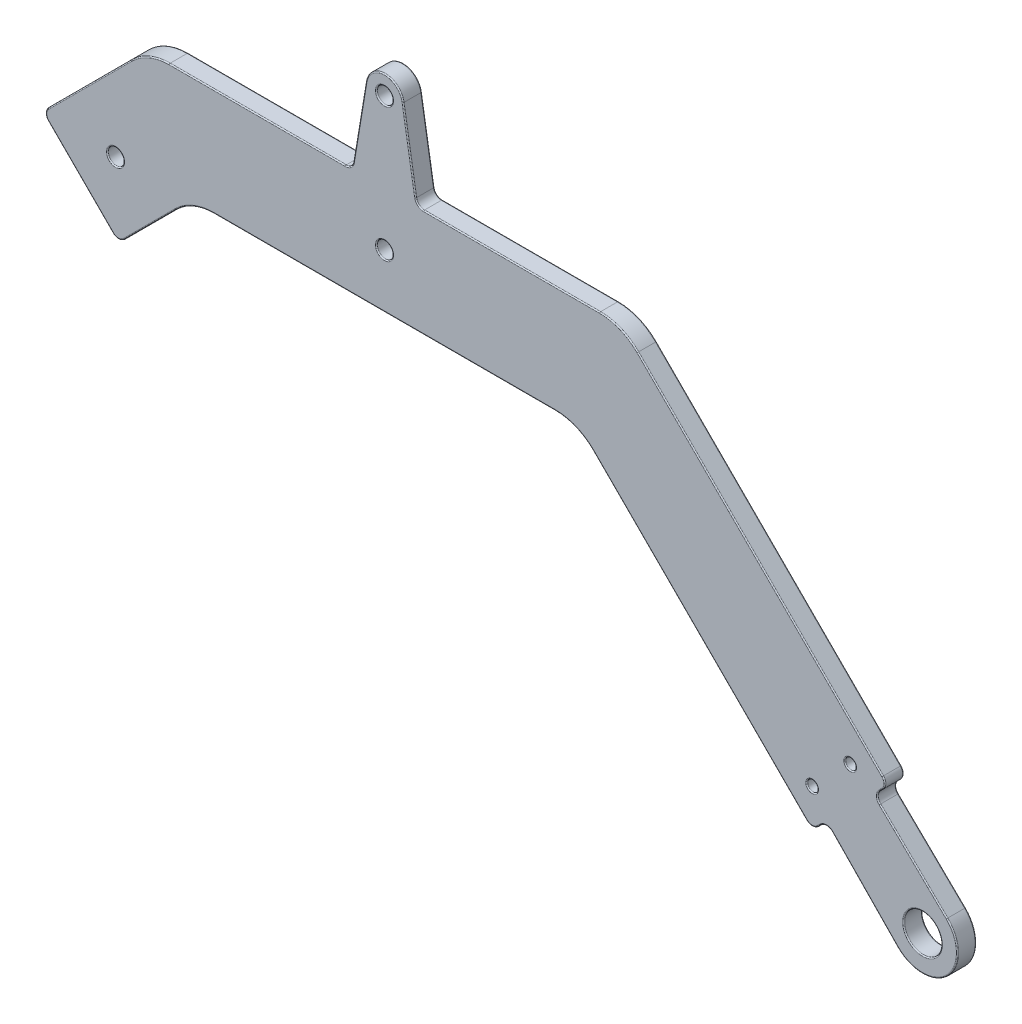
SolidWorks part; units mm, degrees
ref_plane "Front Plane" through (0, 0, 0) normal (0, 0, 1) x (1, 0, 0)
ref_plane "Top Plane" through (0, 0, 0) normal (0, 1, 0) x (1, 0, 0)
ref_plane "Right Plane" through (0, 0, 0) normal (1, 0, 0) x (0, 0, -1)
sketch "Sketch1" plane through (0, 0, 0) normal (0, 0, 1) x (1, 0, 0)
  line L0 (-100, 0) -> (100, 0) construction
  line L1 (-100, 0) -> (0, 100) construction
  line L2 (0, 100) -> (100, 0) construction
  line L3 (0, 0) -> (-50, 50) construction
  line L4 (-40, 60) -> (40, 60) construction
  line L5 (0, 100) -> (0, 60) construction
  circle A0 centre (-100, 0) radius 20
  circle A1 centre (0, 0) radius 20
  circle A2 centre (100, 0) radius 20
  point P2 (0, 0)
  dimension "D5" = 40
  dimension "D1" = 200
  dimension "D2" = 90
  dimension "D3" = 90
  dimension "D4" = 80
sketch "Sketch2" plane through (0, 0, 0) normal (0, 0, 1) x (1, 0, 0)
  line L0 (-56.5165, 43.4835) -> (-40, 60) construction
  line L1 (-100, 0) -> (0, 100) construction
  line L2 (-40, 60) -> (40, 60) construction
  line L3 (40, 60) -> (86.565, 13.435) construction
  line L4 (0, 100) -> (100, 0) construction
  line L5 (-49.4454, 36.4124) -> (-35.8579, 50)
  line L6 (-35.8579, 50) -> (35.8579, 50)
  line L7 (35.8579, 50) -> (79.4939, 6.364)
  line L8 (-63.5876, 50.5546) -> (-44.1421, 70)
  line L9 (-44.1421, 70) -> (44.1421, 70)
  line L10 (44.1421, 70) -> (93.636, 20.5061)
  line L11 (-63.5876, 50.5546) -> (-49.4454, 36.4124)
  line L12 (93.636, 20.5061) -> (79.4939, 6.364)
  line L13 (90.9809, 17.8509) -> (104.534, 4.6576)
  line L14 (82.1491, 9.0191) -> (95.3424, -4.534)
  line L15 (90.1005, 24.0416) -> (75.9584, 9.8995)
  line L16 (0, 100) -> (0, 60) construction
  line L17 (-6, 70) -> (-3.4532, 85.4203)
  line L18 (6, 70) -> (3.4532, 85.4203)
  circle A0 centre (100, 0) radius 3.5
  circle A1 centre (100, 0) radius 10 construction
  arc A2 (95.3424, -4.534) -> (104.534, 4.6576) centre (100, 0) ccw
  circle A3 centre (100, 0) radius 0.5
  circle A4 centre (100, 0) radius 20 construction
  circle A5 centre (100, 0) radius 6.5 construction
  circle A6 centre (79.4939, 13.435) radius 1
  circle A7 centre (86.565, 20.5061) radius 1
  circle A8 centre (0, 60) radius 1.5
  circle A9 centre (0, 84.85) radius 1.5
  arc A10 (3.4532, 85.4203) -> (-3.4532, 85.4203) centre (0, 84.85) ccw
  circle A11 centre (0, 84.85) radius 3.5 construction
  circle A12 centre (-50, 50) radius 1.5
  point P51 (0, 0)
  dimension "D4" = 20
  dimension "D5" = 7
  dimension "D10" = 2
  dimension "D13" = 3
  dimension "D18" = 3
  dimension "D3" = 27.5
  dimension "D8" = 19
  dimension "D9" = 5
  dimension "D11" = 5
  dimension "D12" = 5
  dimension "D14" = 14.85
  dimension "D16" = 6
  dimension "D17" = 6
  dimension "D1" = 10
  dimension "D2" = 10
  dimension "D6" = 3
  dimension "D7" = 3
  dimension "D15" = 2
sketch "Sketch3" plane through (0, 0, 0) normal (0, 0, 1) x (1, 0, 0)
  line L1 (-100, 0) -> (0, 100) construction
  line L2 (-86.565, 13.435) -> (-50, 50) construction
  line L3 (-50, 50) -> (-13.435, 13.435) construction
  line L4 (0, 0) -> (-50, 50) construction
  line L5 (-93.636, 20.5061) -> (-50, 64.1421)
  line L6 (-50, 64.1421) -> (-6.364, 20.5061)
  line L7 (-79.4939, 6.364) -> (-50, 35.8579)
  line L8 (-50, 35.8579) -> (-20.5061, 6.364)
  line L9 (-93.636, 20.5061) -> (-50, 64.1421) construction
  line L10 (-79.4939, 6.364) -> (-50, 35.8579) construction
  line L11 (-93.636, 20.5061) -> (-79.4939, 6.364)
  line L12 (-6.364, 20.5061) -> (-20.5061, 6.364)
  line L13 (-104.5962, 4.5962) -> (-91.2218, 17.9706)
  line L14 (-95.4038, -4.5962) -> (-82.0294, 8.7782)
  line L15 (-17.9706, 8.7782) -> (-4.5962, -4.5962)
  line L16 (-8.7782, 17.9706) -> (4.5962, 4.5962)
  line L17 (-90.1005, 24.0416) -> (-75.9584, 9.8995) construction
  line L18 (-24.0416, 9.8995) -> (-9.8995, 24.0416) construction
  circle A0 centre (-100, 0) radius 10 construction
  circle A1 centre (-100, 0) radius 3.5
  circle A2 centre (0, 0) radius 3.5
  circle A3 centre (0, 0) radius 10 construction
  arc A4 (-4.5962, -4.5962) -> (4.5962, 4.5962) centre (0, 0) ccw
  arc A5 (-104.5962, 4.5962) -> (-95.4038, -4.5962) centre (-100, 0) ccw
  circle A6 centre (-86.565, 20.5061) radius 1
  circle A7 centre (-100, 0) radius 20 construction
  circle A8 centre (0, 0) radius 20 construction
  circle A9 centre (-100, 0) radius 6.5 construction
  circle A10 centre (0, 0) radius 6.5 construction
  circle A11 centre (-79.4939, 13.435) radius 1
  circle A12 centre (-20.5061, 13.435) radius 1
  circle A13 centre (-13.435, 20.5061) radius 1
  circle A14 centre (-50, 50) radius 1.5 construction
  circle A15 centre (-50, 50) radius 1.5
  point P55 (0, 0)
  dimension "D1" = 20
  dimension "D2" = 7
  dimension "D8" = 2
  dimension "D6" = 19
  dimension "D7" = 19
  dimension "D9" = 5
  dimension "D10" = 5
  dimension "D11" = 5
  dimension "D12" = 5
  dimension "D13" = 5
  dimension "D14" = 5
  dimension "D3" = 3
  dimension "D4" = 10
  dimension "D5" = 10
sketch "Sketch4" plane through (0, 0, 0) normal (0, 0, 1) x (1, 0, 0)
  line L0 (-57.5, 94.8011) -> (57.5, 94.8011)
  line L1 (57.5, 94.8011) -> (57.5, 84.8011)
  line L2 (57.5, 84.8011) -> (44.1421, 70)
  line L3 (44.1421, 70) -> (-44.1421, 70)
  line L4 (-44.1421, 70) -> (-57.5, 84.8011)
  line L5 (-57.5, 84.8011) -> (-57.5, 94.8011)
  line L6 (4, 60) -> (4, 70)
  line L7 (-4, 60) -> (-4, 70)
  line L9 (-22.5, 86.3011) -> (22.5, 86.3011) construction
  line L10 (-22.5, 90.8011) -> (22.5, 90.8011)
  line L11 (-22.5, 81.8011) -> (22.5, 81.8011)
  circle A0 centre (0, 60) radius 1.5 construction
  circle A1 centre (0, 60) radius 1.5
  arc A2 (-4, 60) -> (4, 60) centre (0, 60) ccw
  circle A3 centre (0, 60) radius 4 construction
  arc A4 (-22.5, 90.8011) -> (-22.5, 81.8011) centre (-22.5, 86.3011) ccw
  arc A5 (22.5, 81.8011) -> (22.5, 90.8011) centre (22.5, 86.3011) ccw
  point P19 (0, 86.3011)
  point P24 (0, 0)
  point P25 (0, 0)
  point P27 (0, 0)
  dimension "D1" = 115
  dimension "D2" = 10
  dimension "D3" = 2.5
  dimension "D4" = 45
  dimension "D5" = 9
  dimension "D6" = 4
sketch "Sketch6" plane through (0, 0, 0) normal (0, 0, 1) x (1, 0, 0)
  line L1 (90.9809, 17.8509) -> (104.534, 4.6576) construction
  line L2 (82.1491, 9.0191) -> (95.3424, -4.534) construction
  line L3 (-6, 70) -> (-3.4532, 85.4203) construction
  line L4 (6, 70) -> (3.4532, 85.4203) construction
  line L6 (90.9809, 17.8509) -> (104.534, 4.6576)
  line L7 (82.1491, 9.0191) -> (95.3424, -4.534)
  line L8 (93.636, 20.5061) -> (44.1421, 70)
  line L9 (79.4939, 6.364) -> (93.636, 20.5061)
  line L10 (35.8579, 50) -> (79.4939, 6.364)
  line L11 (-35.8579, 50) -> (35.8579, 50)
  line L12 (-49.4454, 36.4124) -> (-35.8579, 50)
  line L13 (-63.5876, 50.5546) -> (-49.4454, 36.4124)
  line L14 (-44.1421, 70) -> (-63.5876, 50.5546)
  line L15 (44.1421, 70) -> (-44.1421, 70)
  line L16 (93.636, 20.5061) -> (44.1421, 70)
  line L17 (79.4939, 6.364) -> (82.1491, 9.0191)
  line L18 (35.8579, 50) -> (79.4939, 6.364)
  line L19 (-35.8579, 50) -> (35.8579, 50)
  line L20 (-49.4454, 36.4124) -> (-35.8579, 50)
  line L21 (-63.5876, 50.5546) -> (-49.4454, 36.4124)
  line L22 (-44.1421, 70) -> (-63.5876, 50.5546)
  line L23 (44.1421, 70) -> (6, 70)
  line L24 (-6, 70) -> (-3.4532, 85.4203)
  line L25 (6, 70) -> (3.4532, 85.4203)
  line L26 (-6, 70) -> (-44.1421, 70)
  line L27 (90.9809, 17.8509) -> (93.636, 20.5061)
  arc A0 (95.3424, -4.534) -> (104.534, 4.6576) centre (100, 0) ccw construction
  circle A1 centre (100, 0) radius 0.5
  circle A2 centre (100, 0) radius 0.5
  circle A3 centre (100, 0) radius 3.5
  circle A4 centre (100, 0) radius 3.5
  circle A5 centre (0, 84.85) radius 1.5
  circle A6 centre (0, 84.85) radius 1.5
  circle A7 centre (0, 60) radius 1.5
  circle A8 centre (0, 60) radius 1.5
  circle A9 centre (86.565, 20.5061) radius 1
  circle A10 centre (86.565, 20.5061) radius 1
  circle A11 centre (79.4939, 13.435) radius 1
  circle A12 centre (79.4939, 13.435) radius 1
  circle A13 centre (-50, 50) radius 1.5
  circle A14 centre (-50, 50) radius 1.5
  arc A15 (3.4532, 85.4203) -> (-3.4532, 85.4203) centre (0, 84.85) ccw construction
  arc A16 (95.3424, -4.534) -> (104.534, 4.6576) centre (100, 0) ccw
  arc A17 (3.4532, 85.4203) -> (-3.4532, 85.4203) centre (0, 84.85) ccw
  dimension "D1" = 0
  dimension "D2" = 0
  dimension "D3" = 0
  dimension "D4" = 0
  dimension "D5" = 0
  dimension "D6" = 0
  dimension "D7" = 0
  dimension "D8" = 0
extrude "Boss-Extrude1" add sketch "Sketch6" along normal blind 3.5 contours L25 A17 L24 L26 L22 L21 L20 L19 L18 L17 L7 A16 L6 L27 L16 L23 A4 A6 A8 A10 A12 A14
fillet "Fillet1" radius 10 4 edges at (35.8579, 50, 1.75) (-35.8579, 50, 1.75) (-44.1421, 70, 1.75) (44.1421, 70, 1.75)
fillet "Fillet2" radius 1.5 8 edges at (-49.4454, 36.4124, 1.75) (-63.5876, 50.5546, 1.75) (-6, 70, 1.75) (6, 70, 1.75) (90.9809, 17.8509, 1.75) (82.1491, 9.0191, 1.75) (79.4939, 6.364, 1.75) (93.636, 20.5061, 1.75)
fillet "Fillet3" radius 0.2 68 edges at (103.5, 0, 0) (1.5, 84.85, 0) (1.5, 60, 0) (87.565, 20.5061, 0) (80.4939, 13.435, 0) (-48.5, 50, 0) (4.6229, 78.3379, 0) (0, 88.35, 0) (-4.6229, 78.3379, 0) (-23.6363, 70, 0) (-54.799, 59.3431, 0) (-56.5165, 43.4835, 0) (-43.5858, 42.2721, 0) (0, 50, 0) (58.61, 27.2478, 0) (80.8143, 7.6844, 0) (89.276, 1.6979, 0) (104.5962, -4.5962, 0) (98.3021, 10.724, 0) (92.3156, 19.1857, 0) (69.8232, 44.3189, 0) (23.6363, 70, 0) (103.5, 0, 3.5) (1.5, 84.85, 3.5) (1.5, 60, 3.5) (87.565, 20.5061, 3.5) (80.4939, 13.435, 3.5) (-48.5, 50, 3.5) (4.6229, 78.3379, 3.5) (0, 88.35, 3.5) (-4.6229, 78.3379, 3.5) (-23.6363, 70, 3.5) (-54.799, 59.3431, 3.5) (-56.5165, 43.4835, 3.5) (-43.5858, 42.2721, 3.5) (0, 50, 3.5) (58.61, 27.2478, 3.5) (80.8143, 7.6844, 3.5) (89.276, 1.6979, 3.5) (104.5962, -4.5962, 3.5) (98.3021, 10.724, 3.5) (92.3156, 19.1857, 3.5) (69.8232, 44.3189, 3.5) (43.8268, 69.2388, 0) (-43.8268, 69.2388, 0) (43.8268, 69.2388, 3.5) (-43.8268, 69.2388, 3.5) (35.5426, 49.2388, 0) (35.5426, 49.2388, 3.5) (-35.5426, 49.2388, 0) (-35.5426, 49.2388, 3.5) (93.0147, 20.5061, 0) (79.4939, 6.9853, 0) (-62.9663, 50.5546, 0) (-49.4454, 37.0337, 0) (93.0147, 20.5061, 3.5) (79.4939, 6.9853, 3.5) (-62.9663, 50.5546, 3.5) (-49.4454, 37.0337, 3.5) (-6.3022, 70.3562, 0) (-6.3022, 70.3562, 3.5) (6.3022, 70.3562, 0) (6.3022, 70.3562, 3.5) (91.6166, 17.8552, 0) (91.6166, 17.8552, 3.5) (82.1448, 8.3834, 0) (82.1448, 8.3834, 3.5) (23.6363, 70, 3.5)
